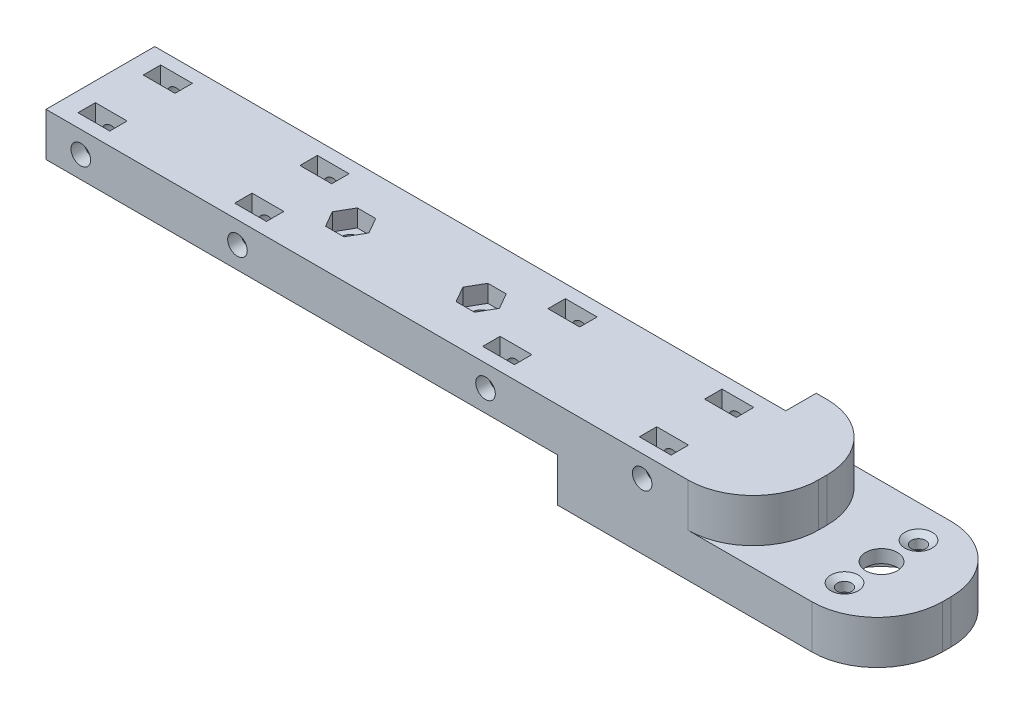
SolidWorks part; units mm, degrees
ref_plane "Front Plane" through (0, 0, 0) normal (0, 0, 1) x (1, 0, 0)
ref_plane "Top Plane" through (0, 0, 0) normal (0, 1, 0) x (1, 0, 0)
ref_plane "Right Plane" through (0, 0, 0) normal (1, 0, 0) x (0, 0, -1)
sketch "Sketch1" plane through (0, 0, 0) normal (0, 1, 0) x (1, 0, 0)
  line L7 (0, 0) -> (145, 0)
  line L8 (0, 0) -> (0, 25)
  line L9 (0, 25) -> (145, 25)
  line L10 (145, 0) -> (145, 25)
  dimension "D1" = 25
  dimension "D3" = 145
extrude "Boss-Extrude1" add sketch "Sketch1" along normal blind 10
sketch "Sketch2" plane through (0, 10, 0) normal (0, 1, 0) x (1, 0, 0)
  line L5 (145, 0) -> (162.5, 0)
  line L6 (145, 0) -> (145, 32)
  line L7 (145, 32) -> (162.5, 32)
  line L8 (162.5, 0) -> (162.5, 32)
  dimension "D1" = 17.5
  dimension "D2" = 32
extrude "Boss-Extrude2" add sketch "Sketch2" against normal blind 10
sketch "Sketch4" plane through (0, 0, 0) normal (0, -1, 0) x (1, 0, 0)
  line L0 (162.5, -32) -> (191, -32) construction
  line L1 (162.5, 0) -> (117.5, 0) construction
  line L2 (0, 0) -> (162.5, 0) construction
  line L4 (117.5, 0) -> (191, 0)
  line L5 (117.5, 0) -> (117.5, -32)
  line L6 (117.5, -32) -> (191, -32)
  line L7 (191, 0) -> (191, -32)
  dimension "D1" = 28.5
  dimension "D2" = 45
extrude "Boss-Extrude3" add sketch "Sketch4" along normal blind 10
sketch "Sketch8" plane through (0, 0, -25) normal (0, 0, -1) x (-1, 0, 0)
  line L0 (-145, 5) -> (0, 5) construction
  line L1 (-145, 10) -> (-145, 0) construction
  line L2 (0, 10) -> (0, 0) construction
  line L3 (-72.5, 10) -> (-72.5, 0) construction
  line L4 (0, 10) -> (-145, 10) construction
  line L5 (0, 0) -> (-117.5, 0) construction
  circle A0 centre (-137, 5) radius 2.25
  circle A1 centre (-101, 5) radius 2.25
  circle A2 centre (-44, 5) radius 2.25
  circle A3 centre (-8, 5) radius 2.25
  dimension "D1" = 8
  dimension "D2" = 4.5
  dimension "D4" = 36
  dimension "D3" = 2
extrude "Cut-Extrude5" cut sketch "Sketch8" against normal through all
sketch "Sketch9" plane through (0, 10, 0) normal (0, 1, 0) x (1, 0, 0)
  line L0 (145, 25) -> (145, 0) construction
  line L1 (0, 0) -> (162.5, 0) construction
  line L2 (145, 12.5) -> (0, 12.5) construction
  line L3 (0, 0) -> (0, 25) construction
  line L4 (72.5, 25) -> (72.5, 0) construction
  line L5 (0, 25) -> (145, 25) construction
  line L6 (137, 0) -> (137, 25) construction
  line L7 (140.65, 22) -> (133.35, 22)
  line L8 (140.65, 7) -> (133.35, 7)
  line L9 (140.65, 7) -> (140.65, 3)
  line L10 (140.65, 3) -> (133.35, 3)
  line L11 (133.35, 7) -> (133.35, 3)
  line L12 (140.65, 7) -> (133.35, 3) construction
  line L13 (140.65, 3) -> (133.35, 7) construction
  line L14 (133.35, 18) -> (133.35, 22)
  line L15 (140.65, 18) -> (133.35, 18)
  line L16 (140.65, 18) -> (140.65, 22)
  line L17 (104.65, 7) -> (104.65, 3)
  line L18 (104.65, 7) -> (97.35, 7)
  line L19 (97.35, 7) -> (97.35, 3)
  line L20 (104.65, 3) -> (97.35, 3)
  line L21 (104.65, 22) -> (97.35, 22)
  line L22 (97.35, 18) -> (97.35, 22)
  line L23 (104.65, 18) -> (97.35, 18)
  line L24 (104.65, 18) -> (104.65, 22)
  line L25 (4.35, 18) -> (4.35, 22)
  line L26 (4.35, 18) -> (11.65, 18)
  line L27 (11.65, 18) -> (11.65, 22)
  line L28 (4.35, 22) -> (11.65, 22)
  line L29 (40.35, 18) -> (40.35, 22)
  line L30 (40.35, 18) -> (47.65, 18)
  line L31 (47.65, 18) -> (47.65, 22)
  line L32 (40.35, 22) -> (47.65, 22)
  line L33 (40.35, 7) -> (47.65, 7)
  line L34 (47.65, 7) -> (47.65, 3)
  line L35 (40.35, 3) -> (47.65, 3)
  line L36 (40.35, 7) -> (40.35, 3)
  line L37 (4.35, 3) -> (11.65, 3)
  line L38 (11.65, 7) -> (11.65, 3)
  line L39 (4.35, 7) -> (11.65, 7)
  line L40 (4.35, 7) -> (4.35, 3)
  point P15 (137, 5)
  dimension "D1" = 8
  dimension "D2" = 5
  dimension "D3" = 7.3
  dimension "D4" = 4
  dimension "D6" = 36
  dimension "D5" = 2
extrude "Cut-Extrude6" cut sketch "Sketch9" against normal up to surface (10 mm away) up to face at (58.75, 0, -12.5)
sketch "Sketch10" plane through (0, 0, 0) normal (0, 1, 0) x (1, 0, 0)
  line L0 (191, 16) -> (162.5, 16) construction
  line L1 (191, 32) -> (191, 0) construction
  line L2 (162.5, 0) -> (162.5, 32) construction
  circle A0 centre (176, 16) radius 3.65
  dimension "D1" = 15
  dimension "D2" = 7.3
extrude "Cut-Extrude7" cut sketch "Sketch10" against normal up to next
sketch "Sketch11" plane through (0, -10, 0) normal (0, -1, 0) x (1, 0, 0)
  circle A0 centre (176, -16) radius 12.75
  dimension "D1" = 25.5
extrude "Cut-Extrude8" cut sketch "Sketch11" against normal blind 7
sketch "Sketch14" plane through (0, -3, 0) normal (0, -1, 0) x (1, 0, 0)
  line L0 (176, -16) -> (176, -3.25) construction
  line L1 (163.25, -16) -> (188.75, -16) construction
  circle A0 centre (176, -16) radius 12.75 construction
  circle A1 centre (176, -7.5) radius 1.65
  circle A2 centre (176, -16) radius 12.75 construction
  circle A3 centre (176, -24.5) radius 1.65
  dimension "D1" = 3.3
  dimension "D2" = 8.5
extrude "Cut-Extrude11" cut sketch "Sketch14" against normal up to next
chamfer "Chamfer1" distance 1.5 angle 30 2 edges at (176, 0, -26.15) (176, 0, -9.15)
fillet "Fillet1" radius 15 4 edges at (162.5, 5, 0) (162.5, 5, -32) (191, -5, -32) (191, -5, 0)
sketch "Sketch15" plane through (0, 10, 0) normal (0, 1, 0) x (1, 0, 0)
  line L0 (0, 12.5) -> (162.2902, 12.5) construction
  line L1 (0, 0) -> (0, 25) construction
  arc A0 (147.5, 0) -> (162.5, 15) centre (147.5, 15) ccw construction
  circle A1 centre (57.5, 12.5) radius 2.25
  circle A2 centre (87.5, 12.5) radius 2.25
  dimension "D1" = 57.5
  dimension "D2" = 4.5
  dimension "D4" = 30
  dimension "D3" = 2
extrude "Cut-Extrude12" cut sketch "Sketch15" against normal through all
sketch "Sketch16" plane through (0, 10, 0) normal (0, 1, 0) x (1, 0, 0)
  line L0 (91.7147, 12.5) -> (89.6073, 16.15)
  line L1 (61.7147, 12.5) -> (59.6073, 16.15)
  line L2 (59.6073, 16.15) -> (55.3927, 16.15)
  line L3 (55.3927, 16.15) -> (53.2853, 12.5)
  line L4 (53.2853, 12.5) -> (55.3927, 8.85)
  line L5 (55.3927, 8.85) -> (59.6073, 8.85)
  line L6 (59.6073, 8.85) -> (61.7147, 12.5)
  line L7 (89.6073, 16.15) -> (85.3927, 16.15)
  line L8 (85.3927, 16.15) -> (83.2853, 12.5)
  line L9 (83.2853, 12.5) -> (85.3927, 8.85)
  line L10 (85.3927, 8.85) -> (89.6073, 8.85)
  line L11 (89.6073, 8.85) -> (91.7147, 12.5)
  circle A0 centre (57.5, 12.5) radius 3.65 construction
  dimension "D1" = 7.3
  dimension "D2" = 3.65
  dimension "D4" = 30
  dimension "D3" = 2
extrude "Cut-Extrude13" cut sketch "Sketch16" against normal blind 4
